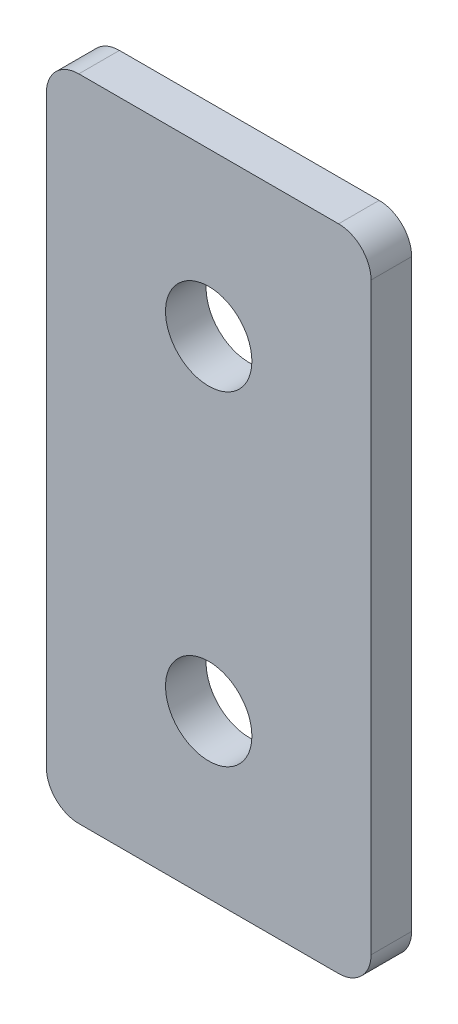
SolidWorks part; units mm, degrees
ref_plane "Front Plane" through (0, 0, 0) normal (0, 0, 1) x (1, 0, 0)
ref_plane "Top Plane" through (0, 0, 0) normal (0, 1, 0) x (1, 0, 0)
ref_plane "Right Plane" through (0, 0, 0) normal (1, 0, 0) x (0, 0, -1)
sketch "Sketch1" plane through (0, 0, 0) normal (0, 0, 1) x (1, 0, 0)
  line L0 (-12.7, 25.4) -> (-12.7, 12.7) construction
  line L1 (-10.16, -25.4) -> (10.16, -25.4)
  line L2 (-12.7, -22.86) -> (-12.7, 22.86)
  line L3 (-10.16, 25.4) -> (10.16, 25.4)
  line L4 (12.7, -22.86) -> (12.7, 22.86)
  line L5 (-12.7, -25.4) -> (12.7, 25.4) construction
  line L6 (-12.7, 25.4) -> (12.7, -25.4) construction
  line L7 (-12.7, 12.7) -> (0, 12.7) construction
  line L8 (12.7, -25.4) -> (12.7, -12.7) construction
  line L9 (12.7, -12.7) -> (0, -12.7) construction
  circle A0 centre (0, 12.7) radius 3.3782
  circle A1 centre (0, -12.7) radius 3.3782
  arc A2 (-12.7, 22.86) -> (-10.16, 25.4) centre (-10.16, 22.86) cw
  arc A3 (12.7, 22.86) -> (10.16, 25.4) centre (10.16, 22.86) ccw
  arc A4 (12.7, -22.86) -> (10.16, -25.4) centre (10.16, -22.86) cw
  arc A5 (-12.7, -22.86) -> (-10.16, -25.4) centre (-10.16, -22.86) ccw
  point P0 (0, 0)
  dimension "D2" = 2.54
extrude "Boss-Extrude1" add sketch "Sketch1" along normal blind 3.175
